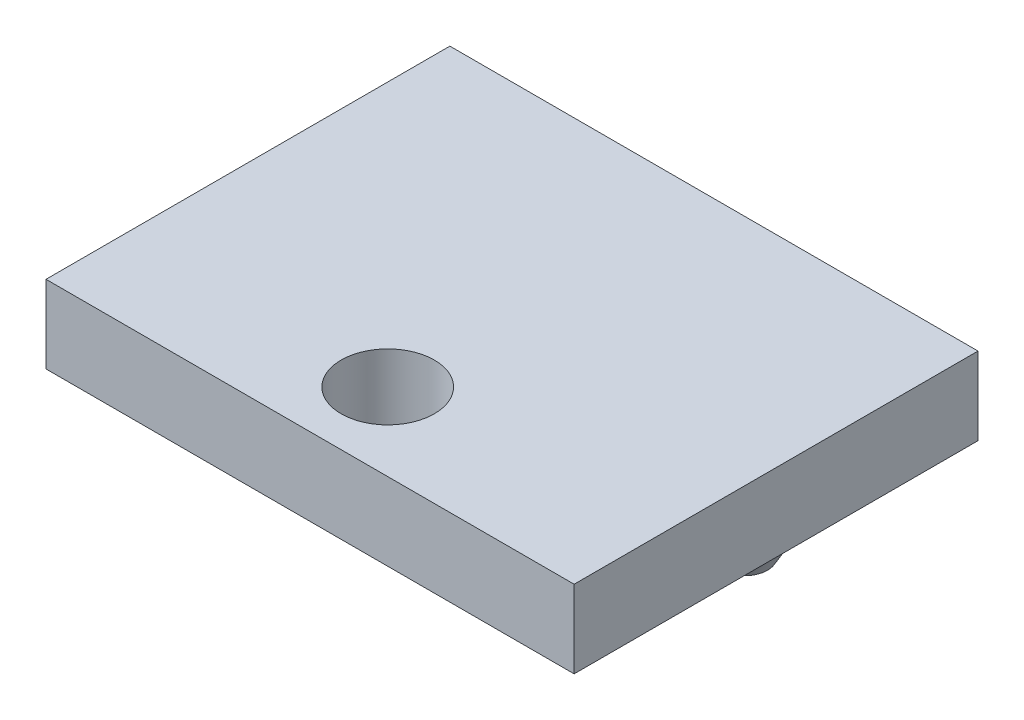
SolidWorks part; units mm, degrees
ref_plane "Front Plane" through (0, 0, 0) normal (0, 0, 1) x (1, 0, 0)
ref_plane "Top Plane" through (0, 0, 0) normal (0, 1, 0) x (1, 0, 0)
ref_plane "Right Plane" through (0, 0, 0) normal (1, 0, 0) x (0, 0, -1)
sketch "Sketch1" plane through (0, 0, 0) normal (0, 1, 0) x (1, 0, 0)
  line L0 (-10, 0) -> (10, 0)
  circle A0 centre (-10, 0) radius 2.45
  circle A1 centre (10, 0) radius 2.45
  point P4 (0, 0)
  point P9 (2.1432, -22.565)
  point P10 (0, 0)
  dimension "D1" = 4.9
  dimension "D2" = 4.9
  dimension "D3" = 20
extrude "Boss-Extrude1" add sketch "Sketch1" against normal blind 6
chamfer "Chamfer1" distance 1 angle 60 1 edges at (10, -6, 2.45)
chamfer "Chamfer2" distance 1 angle 60 1 edges at (-10, -6, 2.45)
sketch "Sketch3" plane through (0, 0, 0) normal (0, 1, 0) x (1, 0, 0)
  line L0 (0, 0) -> (0, -5) construction
  line L1 (-17, 8) -> (17, 8)
  line L2 (-17, 8) -> (-17, -18)
  line L3 (-17, -18) -> (17, -18)
  line L4 (17, 8) -> (17, -18)
  line L5 (-17, 8) -> (17, -18) construction
  line L6 (-17, -18) -> (17, 8) construction
  point P0 (0, -5)
  dimension "D1" = 34
  dimension "D2" = 26
  dimension "D3" = 5
extrude "Boss-Extrude2" add sketch "Sketch3" along normal blind 5
fillet "Fillet1" [suppressed] radius 10
sketch "Sketch5" plane through (0, 0, 0) normal (0, -1, 0) x (1, 0, 0)
  line L0 (-10, 0) -> (10, 0) construction
  circle A0 centre (-10, 0) radius 1.45 construction
sketch "Sketch6" plane through (0, 0, 0) normal (0, -1, 0) x (1, 0, 0)
  line L0 (0, 13) -> (0, 0) construction
  circle A0 centre (0, 13) radius 3
  dimension "D1" = 6
  dimension "D2" = 13
extrude "Cut-Extrude2" cut sketch "Sketch6" against normal through all
